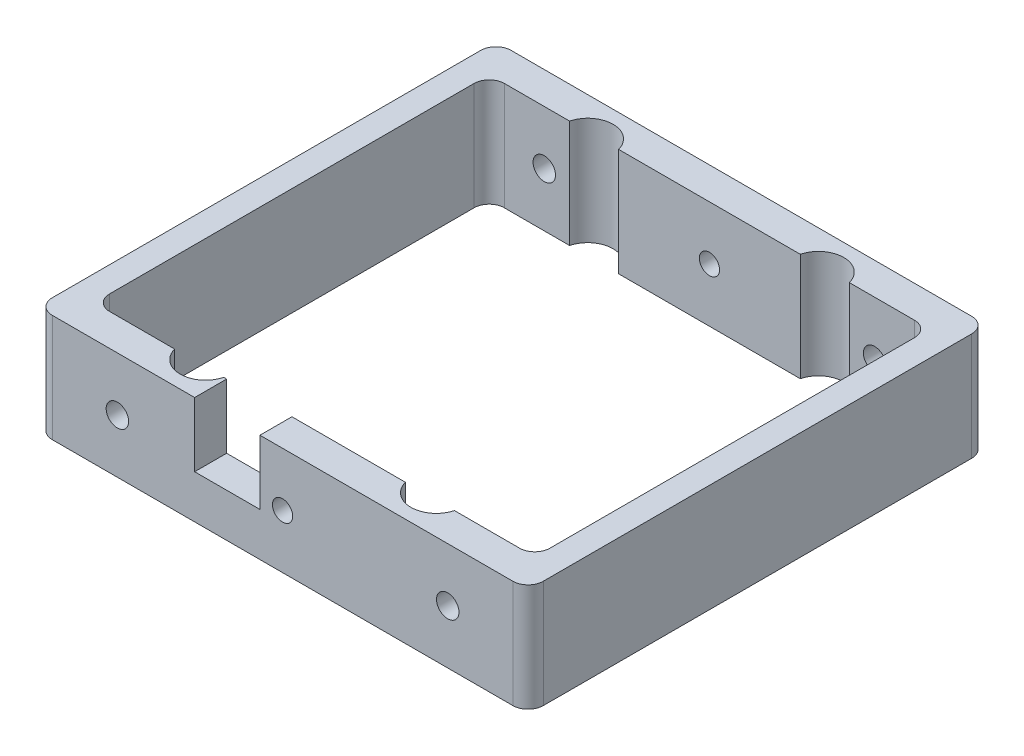
SolidWorks part; units mm, degrees
ref_plane "Front Plane" through (0, 0, 0) normal (0, 0, 1) x (1, 0, 0)
ref_plane "Top Plane" through (0, 0, 0) normal (0, 1, 0) x (1, 0, 0)
ref_plane "Right Plane" through (0, 0, 0) normal (1, 0, 0) x (0, 0, -1)
sketch "Sketch1" plane through (0, 0, 0) normal (0, 1, 0) x (1, 0, 0)
  line L1 (0, 0) -> (60, 0)
  line L2 (0, 0) -> (0, -6.32)
  line L3 (0, -6.32) -> (60, -6.32)
  line L4 (60, 0) -> (60, -6.32)
  dimension "D1" = 60
  dimension "D2" = 6.32
extrude "Boss-Extrude1" add sketch "Sketch1" along normal mid plane 21.28
sketch "Sketch2" plane through (0, 10.64, 0) normal (0, 1, 0) x (1, 0, 0)
  line L0 (0, 0) -> (0, -6.32) construction
  line L1 (0, -6.32) -> (60, -6.32) construction
  line L2 (60, -6.32) -> (60, 0) construction
  circle A0 centre (7.21, 1.25) radius 5
  circle A1 centre (52.79, 1.25) radius 5
  dimension "D1" = 7.21
  dimension "D3" = 7.21
  dimension "D2" = 7.57
  dimension "D4" = 7.57
extrude "Cut-Extrude1" cut sketch "Sketch2" against normal through all
sketch "Sketch3" plane through (60, 0, 0) normal (1, 0, 0) x (0, 0, -1)
  line L1 (-6.32, 10.64) -> (0, 10.64)
  line L2 (-6.32, 10.64) -> (-6.32, -10.64)
  line L3 (-6.32, -10.64) -> (0, -10.64)
  line L4 (0, 10.64) -> (0, -10.64)
extrude "Boss-Extrude2" add sketch "Sketch3" along normal blind 18.5
sketch "Sketch4" plane through (0, 0, 0) normal (-1, 0, 0) x (0, 0, 1)
  line L1 (0, 10.64) -> (6.32, 10.64)
  line L2 (0, 10.64) -> (0, -10.64)
  line L3 (0, -10.64) -> (6.32, -10.64)
  line L4 (6.32, 10.64) -> (6.32, -10.64)
extrude "Boss-Extrude3" add sketch "Sketch4" along normal blind 18.5
sketch "Sketch5" plane through (0, 0, 0) normal (0, 0, -1) x (-1, 0, 0)
  line L5 (-2.3688, -10.64) -> (18.5, -10.64) construction
  line L6 (18.5, 10.64) -> (13.5, 10.64)
  line L7 (18.5, 10.64) -> (18.5, -10.64)
  line L8 (18.5, -10.64) -> (13.5, -10.64)
  line L9 (13.5, 10.64) -> (13.5, -10.64)
  dimension "D1" = 5
extrude "Boss-Extrude6" add sketch "Sketch5" along normal blind 84.33
sketch "Sketch6" plane through (0, 0, 0) normal (0, 0, -1) x (-1, 0, 0)
  line L1 (-78.5, 10.64) -> (-73.5, 10.64)
  line L2 (-78.5, 10.64) -> (-78.5, -10.652)
  line L3 (-78.5, -10.652) -> (-73.5, -10.652)
  line L4 (-73.5, 10.64) -> (-73.5, -10.652)
  dimension "D1" = 5
extrude "Boss-Extrude7" add sketch "Sketch6" along normal blind 84.33
sketch "Sketch7" plane through (73.5, 0, 0) normal (-1, 0, 0) x (0, 0, 1)
  line L0 (-84.33, -10.652) -> (0, -10.652) construction
  line L1 (-84.33, 10.64) -> (-78.01, 10.64)
  line L2 (-84.33, 10.64) -> (-84.33, -10.652)
  line L3 (-84.33, -10.652) -> (-78.01, -10.652)
  line L4 (-78.01, 10.64) -> (-78.01, -10.652)
  dimension "D1" = 6.32
extrude "Boss-Extrude8" add sketch "Sketch7" along normal through all
sketch "Sketch9" plane through (0, 10.64, 0) normal (0, 1, 0) x (1, 0, 0)
  line L0 (-18.5, 84.33) -> (78.5, 84.33) construction
  circle A0 centre (7.21, 76.76) radius 5
  circle A1 centre (52.79, 76.76) radius 5
  dimension "D1" = 7.57
  dimension "D2" = 7.57
  dimension "D3" = 10
extrude "Cut-Extrude2" cut sketch "Sketch9" against normal through all
sketch "Sketch10" plane through (0, 0, -84.33) normal (0, 0, -1) x (-1, 0, 0)
  line L1 (-78.5, -10.64) -> (18.5, -10.64) construction
  line L2 (-30, -10.64) -> (-30, 10.64) construction
  line L3 (18.5, 10.64) -> (-78.5, 10.64) construction
  circle A0 centre (-62.6312, 0.005) radius 2.22
  circle A1 centre (2.6312, 0.005) radius 2.22
  dimension "D1" = 5
  dimension "D2" = 10.645
extrude "Cut-Extrude3" cut sketch "Sketch10" against normal through all
fillet "Fillet1" radius 3 8 edges at (78.5, 0, 6.32) (-18.5, 0, 6.32) (-13.5, 0, 0) (-18.5, -0.006, -84.33) (73.5, 0, 0) (78.5, -0.006, -84.33) (-13.5, 0, -78.01) (73.5, -0.006, -78.01)
sketch "Sketch13" plane through (0, 0, -84.33) normal (0, 0, -1) x (-1, 0, 0)
  line L1 (-75.5, 10.64) -> (-75.5, -10.652) construction
  line L2 (-75.5, -10.64) -> (15.5, -10.64) construction
  circle A0 centre (-30, 0.005) radius 2
  dimension "D1" = 45.5
  dimension "D2" = 10.645
extrude "Cut-Extrude4" cut sketch "Sketch13" against normal through all
sketch "Sketch14" plane through (0, 10.64, 0) normal (0, 1, 0) x (1, 0, 0)
  line L0 (47.9488, 0) -> (12.0512, 0) construction
  line L1 (12.6307, 0) -> (25.5307, 0)
  line L2 (12.6307, 0) -> (12.6307, -6.32)
  line L3 (12.6307, -6.32) -> (25.5307, -6.32)
  line L4 (25.5307, 0) -> (25.5307, -6.32)
  line L5 (-15.5, -6.32) -> (75.5, -6.32) construction
  line L6 (25.5307, -0.42) -> (25.5307, -6.32) construction
extrude "Cut-Extrude5" cut sketch "Sketch14" against normal mid plane 25.4
